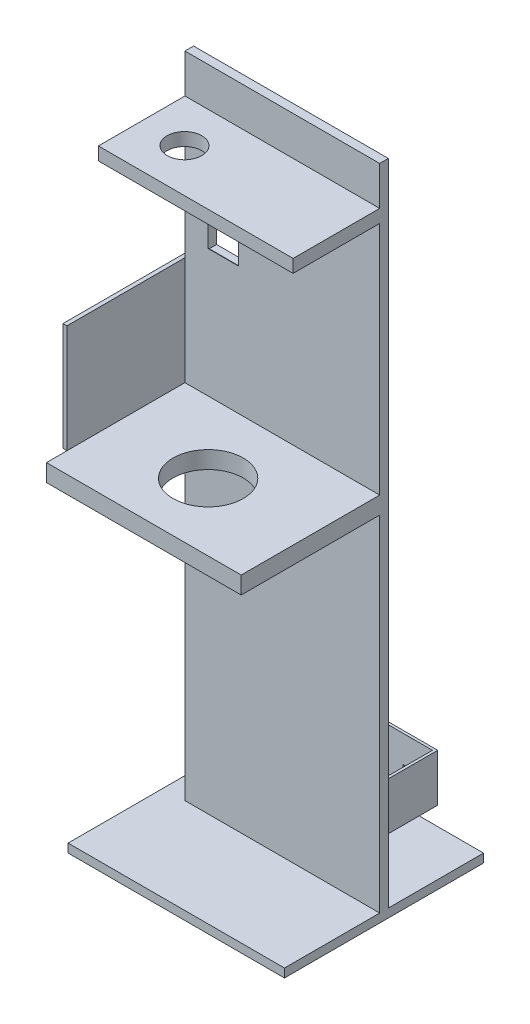
SolidWorks part; units mm, degrees
ref_plane "Alzado" through (0, 0, 0) normal (0, 0, 1) x (1, 0, 0)
ref_plane "Planta" through (0, 0, 0) normal (0, 1, 0) x (1, 0, 0)
ref_plane "Vista lateral" through (0, 0, 0) normal (1, 0, 0) x (0, 0, -1)
sketch "Croquis1" plane through (0, 0, 0) normal (0, 1, 0) x (1, 0, 0)
  line L1 (-138.2849, 137.7589) -> (111.7151, 137.7589)
  line L2 (-138.2849, 137.7589) -> (-138.2849, 17.7589)
  line L3 (-138.2849, 17.7589) -> (111.7151, 17.7589)
  line L4 (111.7151, 137.7589) -> (111.7151, 17.7589)
  dimension "D1" = 250
  dimension "D2" = 120
extrude "Saliente-Extruir1" add sketch "Croquis1" along normal blind 10
sketch "Croquis2" plane through (0, 10, 0) normal (0, 1, 0) x (1, 0, 0)
  line L0 (111.7151, 17.7589) -> (111.7151, 137.7589) construction
  line L1 (-138.2849, 137.7589) -> (111.7151, 137.7589)
  line L2 (-138.2849, 137.7589) -> (-138.2849, 127.7589)
  line L3 (-138.2849, 127.7589) -> (111.7151, 127.7589)
  line L4 (111.7151, 137.7589) -> (111.7151, 127.7589)
  dimension "D1" = 10
extrude "Saliente-Extruir2" add sketch "Croquis2" along normal blind 750
sketch "Croquis3" plane through (0, 0, -137.7589) normal (0, 0, -1) x (-1, 0, 0)
  line L0 (13.2849, 0) -> (13.2849, 98.0434) construction
  line L1 (-81.7219, 59.3565) -> (108.2917, 59.3565)
  line L2 (-81.7219, 59.3565) -> (-81.7219, 54.3565)
  line L3 (-81.7219, 54.3565) -> (108.2917, 54.3565)
  line L4 (108.2917, 59.3565) -> (108.2917, 54.3565)
  line L5 (-81.7219, 59.3565) -> (108.2917, 54.3565) construction
  line L6 (-81.7219, 54.3565) -> (108.2917, 59.3565) construction
  line L7 (-111.7151, 0) -> (138.2849, 0) construction
  point P0 (13.2849, 56.8565)
  dimension "D1" = 5
  dimension "D2" = 190.0137
extrude "Saliente-Extruir3" add sketch "Croquis3" along normal blind 87
sketch "Croquis4" plane through (0, 59.3565, 0) normal (0, 1, 0) x (1, 0, 0)
  line L1 (-19.316, 200.9965) -> (71.3489, 200.9965)
  line L2 (-19.316, 200.9965) -> (-19.316, 141.3513)
  line L3 (-19.316, 141.3513) -> (71.3489, 141.3513)
  line L4 (71.3489, 200.9965) -> (71.3489, 141.3513)
  line L5 (-21.316, 202.9965) -> (73.3489, 202.9965)
  line L6 (-21.316, 202.9965) -> (-21.316, 139.3513)
  line L7 (-21.316, 139.3513) -> (73.3489, 139.3513)
  line L8 (73.3489, 202.9965) -> (73.3489, 139.3513)
  dimension "D1" = 2
  dimension "D2" = 2
  dimension "D3" = 2
  dimension "D4" = 2
extrude "Saliente-Extruir4" add sketch "Croquis4" along normal blind 12
sketch "Croquis5" plane through (0, 59.3565, 0) normal (0, 1, 0) x (1, 0, 0)
  line L0 (81.7219, 137.7589) -> (81.7219, 224.7589)
  line L1 (81.7219, 224.7589) -> (-108.2917, 224.7589)
  line L2 (-108.2917, 224.7589) -> (-108.2917, 137.7589)
  line L3 (-108.2917, 137.7589) -> (81.7219, 137.7589)
  line L4 (78.7219, 141.5129) -> (78.7219, 221.7589)
  line L5 (78.7219, 221.7589) -> (-105.2917, 221.7589)
  line L6 (-105.2917, 221.7589) -> (-105.2917, 141.5129)
  line L8 (78.7219, 141.5129) -> (78.7219, 137.7589)
  line L9 (-105.2917, 141.5129) -> (-105.2917, 137.7589)
  line M9 (-108.2917, 137.7589) -> (81.7219, 137.7589)
  line M10 (81.7219, 137.7589) -> (81.7219, 224.7589)
  line M11 (81.7219, 224.7589) -> (-108.2917, 224.7589)
  line M12 (-108.2917, 224.7589) -> (-108.2917, 137.7589)
  dimension "D1" = 3
  dimension "D2" = 3
  dimension "D3" = 3
extrude "Saliente-Extruir5" add sketch "Croquis5" along normal blind 50 contours L9 L6 L5 L4 L8 L3 M10 M11 M12 M9
sketch "Croquis6" plane through (0, 0, -224.7589) normal (0, 0, -1) x (-1, 0, 0)
  line L1 (-60.9424, 78.0026) -> (-44.3631, 78.0026)
  line L2 (-60.9424, 78.0026) -> (-60.9424, 70.3815)
  line L3 (-60.9424, 70.3815) -> (-44.3631, 70.3815)
  line L4 (-44.3631, 78.0026) -> (-44.3631, 70.3815)
extrude "Cortar-Extruir1" cut sketch "Croquis6" against normal blind 12
sketch "Croquis7" plane through (0, 0, -127.7589) normal (0, 0, 1) x (1, 0, 0)
  line L1 (-86.6662, 606.3352) -> (-51.3223, 606.3352)
  line L2 (-86.6662, 606.3352) -> (-86.6662, 574.7335)
  line L3 (-86.6662, 574.7335) -> (-51.3223, 574.7335)
  line L4 (-51.3223, 606.3352) -> (-51.3223, 574.7335)
  line L5 (-51.2565, 573.6055) -> (-51.2565, 607.6055) construction
extrude "Cortar-Extruir2" cut sketch "Croquis7" against normal blind 12
sketch "Croquis8" plane through (0, 574.7335, 0) normal (0, 1, 0) x (1, 0, 0)
  line L1 (-51.3223, 128.2589) -> (-86.6662, 128.2589)
  line L2 (-51.3223, 128.2589) -> (-51.3223, 127.7589)
  line L3 (-51.3223, 127.7589) -> (-86.6662, 127.7589)
  line L4 (-86.6662, 128.2589) -> (-86.6662, 127.7589)
  dimension "D1" = 0.5
extrude "Saliente-Extruir6" add sketch "Croquis8" along normal blind 1
sketch "Croquis9" plane through (0, 606.3352, 0) normal (0, -1, 0) x (1, 0, 0)
  line L1 (-34.2542, -128.2589) -> (-51.3223, -128.2589)
  line L2 (-34.2542, -128.2589) -> (-34.2542, -127.7589)
  line L3 (-34.2542, -127.7589) -> (-51.3223, -127.7589)
  line L4 (-51.3223, -128.2589) -> (-51.3223, -127.7589)
  dimension "D1" = 0.5
extrude "Saliente-Extruir7" add sketch "Croquis9" along normal blind 1
sketch "Croquis10" plane through (0, 0, -137.7589) normal (0, 0, -1) x (-1, 0, 0)
  line L0 (138.2849, 760) -> (138.2849, 0) construction
  line L1 (-111.7151, 0) -> (138.2849, 0)
  line L2 (-111.7151, 0) -> (-111.7151, 10)
  line L3 (-111.7151, 10) -> (138.2849, 10)
  line L4 (138.2849, 0) -> (138.2849, 10)
  dimension "D1" = 10
extrude "Saliente-Extruir8" add sketch "Croquis10" along normal blind 110
sketch "Croquis11" plane through (0, 0, -127.7589) normal (0, 0, 1) x (1, 0, 0)
  line L0 (-138.2849, 760) -> (-138.2849, 10) construction
  line L1 (-138.2849, 715.0048) -> (111.7151, 715.0048)
  line L2 (-138.2849, 715.0048) -> (-138.2849, 700.0048)
  line L3 (-138.2849, 700.0048) -> (111.7151, 700.0048)
  line L4 (111.7151, 715.0048) -> (111.7151, 700.0048)
  line L5 (111.7151, 760) -> (111.7151, 10) construction
  dimension "D1" = 15
extrude "Saliente-Extruir9" add sketch "Croquis11" along normal blind 100
sketch "Croquis12" plane through (0, 715.0048, 0) normal (0, 1, 0) x (1, 0, 0)
  line L0 (-13.2849, -28.2857) -> (-13.2849, 108.8583) construction
  line L1 (50.0455, 77.7589) -> (-86.6804, 77.7589) construction
  line L2 (111.7151, 27.7589) -> (-138.2849, 27.7589) construction
  line L3 (111.7151, 127.7589) -> (-138.2849, 127.7589) construction
  line L4 (111.7151, 27.7589) -> (111.7151, 127.7589) construction
  line L5 (-138.2849, 27.7589) -> (-138.2849, 127.7589) construction
  circle A0 centre (-63.8423, 77.7589) radius 20
  dimension "D1" = 40
extrude "Cortar-Extruir3" cut sketch "Croquis12" against normal blind 100
sketch "Croquis13" plane through (0, 0, -127.7589) normal (0, 0, 1) x (1, 0, 0)
  line L0 (-138.2849, 700.0048) -> (-138.2849, 10) construction
  line L1 (-138.2849, 428.1884) -> (111.7151, 428.1884)
  line L2 (-138.2849, 428.1884) -> (-138.2849, 408.1884)
  line L3 (-138.2849, 408.1884) -> (111.7151, 408.1884)
  line L4 (111.7151, 428.1884) -> (111.7151, 408.1884)
  line L5 (111.7151, 700.0048) -> (111.7151, 10) construction
  dimension "D1" = 20
extrude "Saliente-Extruir10" add sketch "Croquis13" along normal blind 160
sketch "Croquis14" plane through (0, 428.1884, 0) normal (0, 1, 0) x (1, 0, 0)
  line L0 (-13.2849, -22.0145) -> (-13.2849, 68.9573) construction
  line L1 (111.7151, -32.2411) -> (111.7151, 127.7589) construction
  line L2 (-138.2849, -32.2411) -> (-138.2849, 127.7589) construction
  circle A0 centre (-4.2024, 45.4731) radius 40.595
  point P2 (-13.2849, 45.5719)
  point P9 (-13.2849, 45.4731)
  point P10 (-4.2024, 45.4731)
extrude "Cortar-Extruir4" cut sketch "Croquis14" against normal blind 160
sketch "Croquis15" plane through (0, 0, -137.7589) normal (0, 0, -1) x (-1, 0, 0)
  line L0 (-111.7151, 760) -> (138.2849, 760) construction
  line L6 (138.2849, 10) -> (113.2849, 10)
  line L7 (138.2849, 10) -> (138.2849, 760)
  line L8 (138.2849, 760) -> (113.2849, 760)
  line L9 (113.2849, 10) -> (113.2849, 760)
  dimension "D2" = 25
extrude "Cortar-Extruir5" cut sketch "Croquis15" against normal through all
sketch "Croquis16" plane through (0, 428.1884, 0) normal (0, 1, 0) x (1, 0, 0)
  line L1 (-117.8584, -8.5499) -> (-113.2939, -8.5499)
  line L2 (-117.8584, -8.5499) -> (-117.8584, 137.8982)
  line L3 (-117.8584, 137.8982) -> (-113.2939, 137.8982)
  line L4 (-113.2939, -8.5499) -> (-113.2939, 137.8982)
extrude "Saliente-Extruir11" add sketch "Croquis16" along normal blind 125
